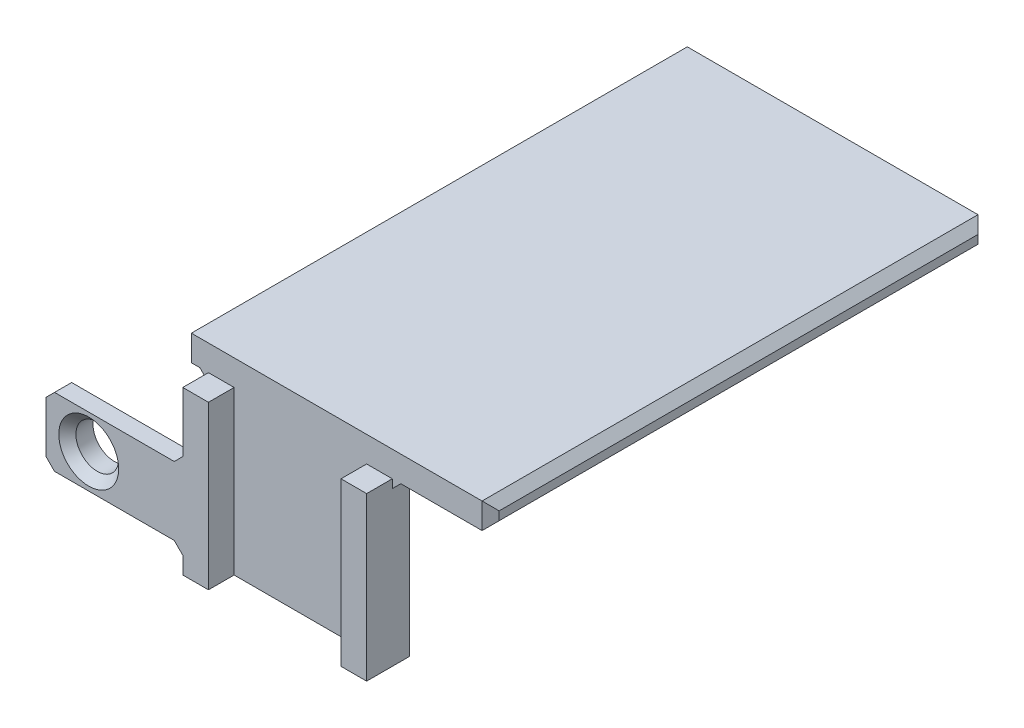
SolidWorks part; units mm, degrees
ref_plane "前视基准面" through (0, 0, 0) normal (0, 0, 1) x (1, 0, 0)
ref_plane "上视基准面" through (0, 0, 0) normal (0, 1, 0) x (1, 0, 0)
ref_plane "右视基准面" through (0, 0, 0) normal (1, 0, 0) x (0, 0, -1)
other "Configuration Table"
sketch "草图1" plane through (0, 0, 0) normal (0, 1, 0) x (1, 0, 0)
  line L0 (-3, 3) -> (18.5, 3)
  line L1 (0, 0) -> (15.5, 0)
  line L2 (0, 0) -> (0, -3)
  line L4 (15.5, 0) -> (15.5, -3)
  line L5 (18.5, 3) -> (18.5, -3)
  line L7 (-3, 3) -> (-3, -3)
  line L8 (0, -3) -> (-3, -3)
  line L9 (15.5, -3) -> (18.5, -3)
  line L10 (18.5, 3) -> (18.5, -6) construction
  line L11 (0, -3) -> (15.5, -3) construction
  line L12 (-3, -6) -> (18.5, -6) construction
  line L13 (-3, 3) -> (-3, -6) construction
  dimension "D1" = 3
  dimension "D2" = 15.5
  dimension "D4" = 3
  dimension "D3" = 3
extrude "凸台-拉伸1" add sketch "草图1" along normal blind 20
sketch "草图2" plane through (0, 0, 3) normal (0, 0, 1) x (1, 0, 0)
  line L0 (-3, 20) -> (-3, 0) construction
  line L1 (-19, 4) -> (-3, 4)
  line L2 (-19, 4) -> (-19, 12)
  line L3 (-19, 12) -> (-3, 12)
  line L4 (-3, 4) -> (-3, 12)
  circle A0 centre (-14.0011, 8.0027) radius 2.503
extrude "凸台-拉伸2" add sketch "草图2" against normal blind 3
sketch "草图3" plane through (0, 0, -3) normal (0, 0, -1) x (-1, 0, 0)
  line L0 (-18.5, 20) -> (3, 20) construction
  line L1 (6, 20) -> (-30, 20)
  line L2 (6, 20) -> (6, 23)
  line L3 (6, 23) -> (-30, 23)
  line L4 (-30, 20) -> (-30, 23)
  line L5 (3, 20) -> (3, 0) construction
  dimension "D1" = 36
  dimension "D2" = 3
  dimension "D3" = 3
extrude "凸台-拉伸3" add sketch "草图3" along normal blind 55 and the other way up to surface
chamfer "倒角1" distance 1 angle 45 30 edges at (30, 23, -29) (30, 21.5, -58) (30, 20, -29) (30, 21.5, 0) (-6, 20, -29) (-6, 21.5, -58) (-6, 23, -29) (-6, 21.5, 0) (-11.4982, 8.0027, 3) (-3, 4, 1.5) (-3, 12, 1.5) (-19, 12, 1.5) (-19, 4, 1.5) (-19, 8, 0) (-11, 4, 0) (-11, 12, 0) (-3, 8, 0) (-3, 20, -1.5) (18.5, 20, -1.5) (7.75, 0, 0) (15.5, 0, 1.5) (17, 0, 3) (18.5, 0, 0) (7.75, 0, -3) (0, 0, 1.5) (-1.5, 0, 3) (-3, 0, 0) (-3, 10, -3) (18.5, 10, -3) (7.75, 20, -3)
